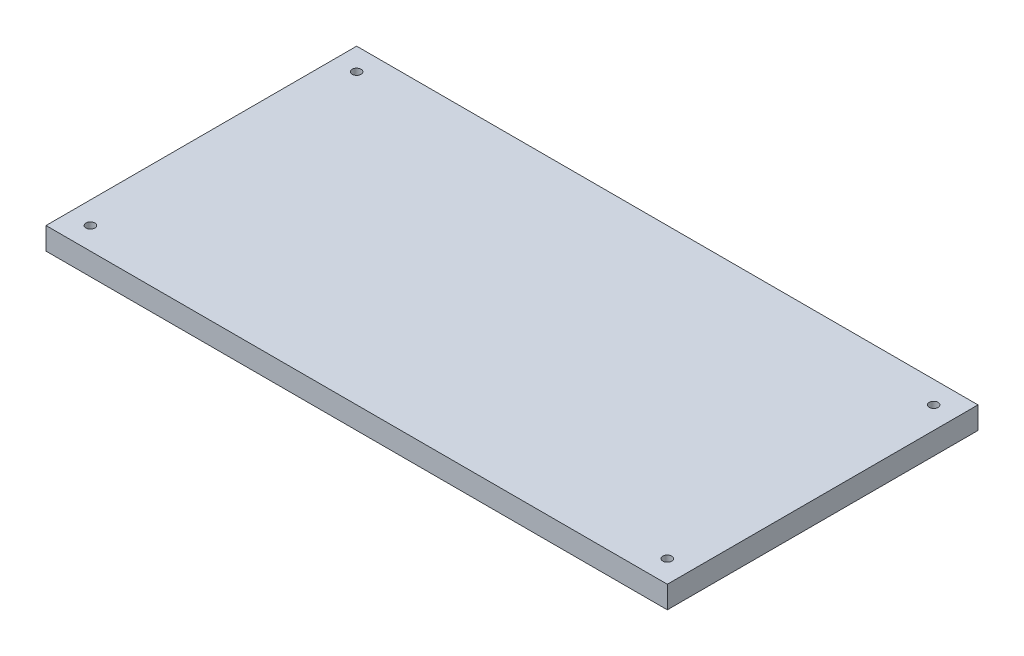
SolidWorks part; units mm, degrees
ref_plane "Płaszczyzna przednia" through (0, 0, 0) normal (0, 0, 1) x (1, 0, 0)
ref_plane "Płaszczyzna górna" through (0, 0, 0) normal (0, 1, 0) x (1, 0, 0)
ref_plane "Płaszczyzna prawa" through (0, 0, 0) normal (1, 0, 0) x (0, 0, -1)
sketch "Szkic1" plane through (0, 0, 0) normal (0, 1, 0) x (1, 0, 0)
  line L0 (70, 0) -> (70, -70) construction
  line L1 (0, 0) -> (140, 0)
  line L2 (0, 0) -> (0, -70)
  line L3 (0, -70) -> (140, -70)
  line L4 (140, 0) -> (140, -70)
  line L5 (0, -35) -> (140, -35) construction
  circle A0 centre (135, -65) radius 1
  circle A1 centre (135, -5) radius 1
  circle A2 centre (5, -5) radius 1
  circle A3 centre (5, -65) radius 1
  dimension "D3" = 2
  dimension "D1" = 140
  dimension "D2" = 70
  dimension "D4" = 5
  dimension "D5" = 5
extrude "Dodanie-wyciągnięcie1" add sketch "Szkic1" along normal blind 5
